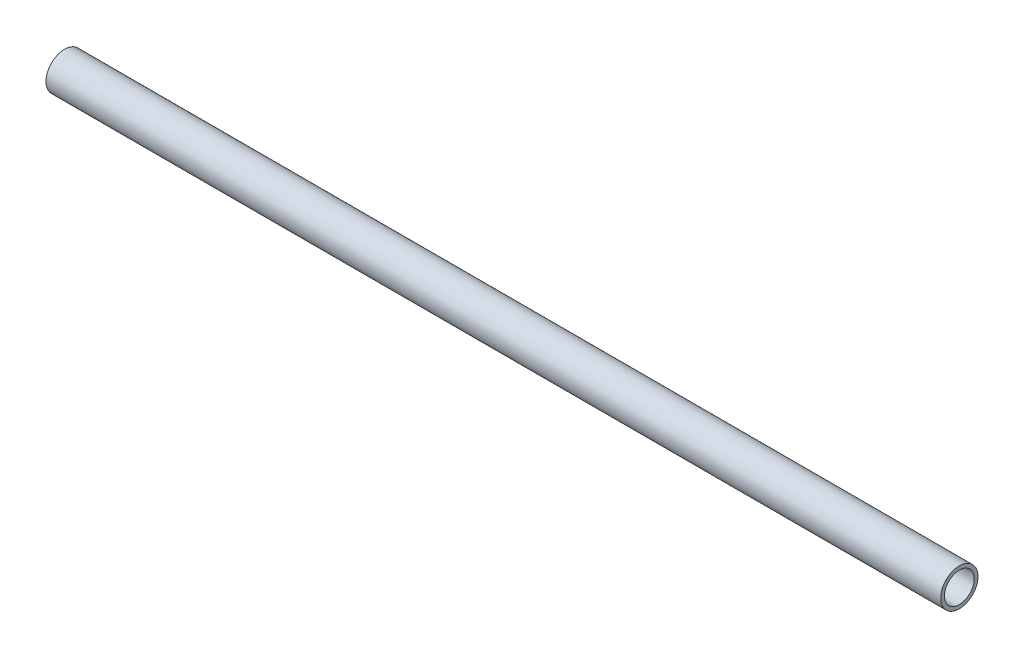
SolidWorks part; units mm, degrees
material "Zoltek Panex 33"
ref_plane "Front Plane" through (0, 0, 0) normal (0, 0, 1) x (1, 0, 0)
ref_plane "Top Plane" through (0, 0, 0) normal (0, 1, 0) x (1, 0, 0)
ref_plane "Right Plane" through (0, 0, 0) normal (1, 0, 0) x (0, 0, -1)
sketch "Sketch1" plane through (0, 0, 0) normal (1, 0, 0) x (0, 0, -1)
  circle A0 centre (0, 0) radius 7.9375
  circle A1 centre (0, 0) radius 6.35
  dimension "D1" = 15.875
  dimension "D2" = 12.7
extrude "Boss-Extrude1" add sketch "Sketch1" along normal mid plane 381
